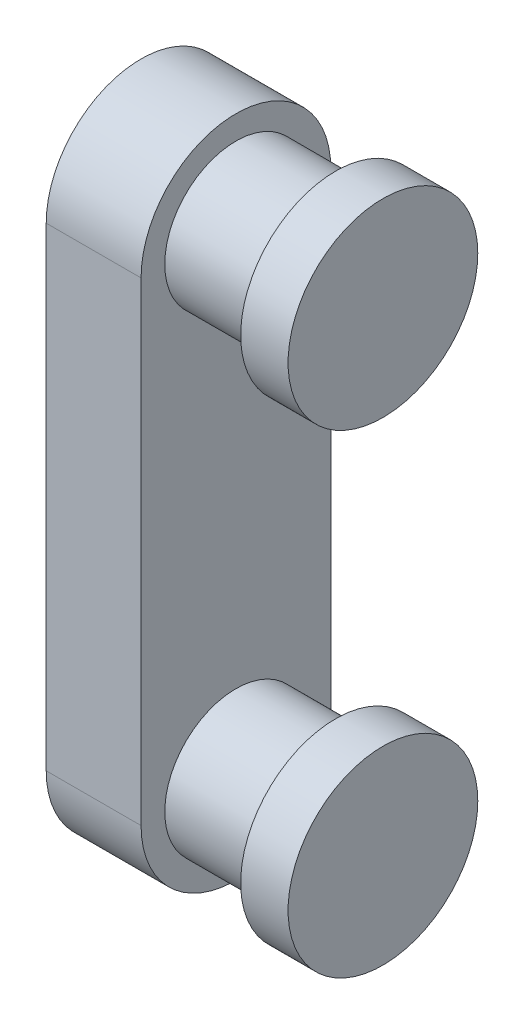
SolidWorks part; units mm, degrees
ref_plane "Plan de face" through (0, 0, 0) normal (0, 0, 1) x (1, 0, 0)
ref_plane "Plan de dessus" through (0, 0, 0) normal (0, 1, 0) x (1, 0, 0)
ref_plane "Plan de droite" through (0, 0, 0) normal (1, 0, 0) x (0, 0, -1)
sketch "Esquisse1" plane through (0, 0, 0) normal (1, 0, 0) x (0, 0, -1)
  line L0 (-27.6742, 69.1855) -> (-2, 5) construction
  line L1 (4.965, 0) -> (-4.3022, 0) construction
  line L2 (2, 5) -> (2, -5)
  line L4 (-2, 5) -> (-2, -5)
  line L5 (2, 5) -> (21.7762, 54.4404) construction
  line L6 (2, -5) -> (0, 0) construction
  line L7 (0, 0) -> (-2, -5) construction
  arc A0 (2, 5) -> (-2, 5) centre (0, 5) ccw
  arc A1 (2, -5) -> (-2, -5) centre (0, -5) cw
  point P0 (0, 0)
  point P6 (0, 40)
  dimension "D1" = 4
  dimension "D2" = 10
extrude "BASE" add sketch "Esquisse1" along normal blind 2
sketch "Esquisse2" plane through (2, 0, 0) normal (1, 0, 0) x (0, 0, -1)
  line L0 (-2, 5) -> (2, 5) construction
  line L1 (2, 5) -> (0, 7) construction
  line L2 (0, 7) -> (0, 39.6014) construction
  arc A0 (2, 5) -> (-2, 5) centre (0, 5) ccw construction
  circle A1 centre (0, 5) radius 1.5
  dimension "D1" = 3
extrude "BOSS FIX" add sketch "Esquisse2" along normal blind 2.1
sketch "Esquisse3" plane through (4.1, 0, 0) normal (1, 0, 0) x (0, 0, -1)
  circle A0 centre (0, 5) radius 2
  dimension "D1" = 4
extrude "BOSS BLOCAGE" add sketch "Esquisse3" along normal blind 1
mirror "SYM FIXATION" about plane through (0, 0, 0) normal (0, 1, 0) of "BOSS BLOCAGE", "BOSS FIX"
